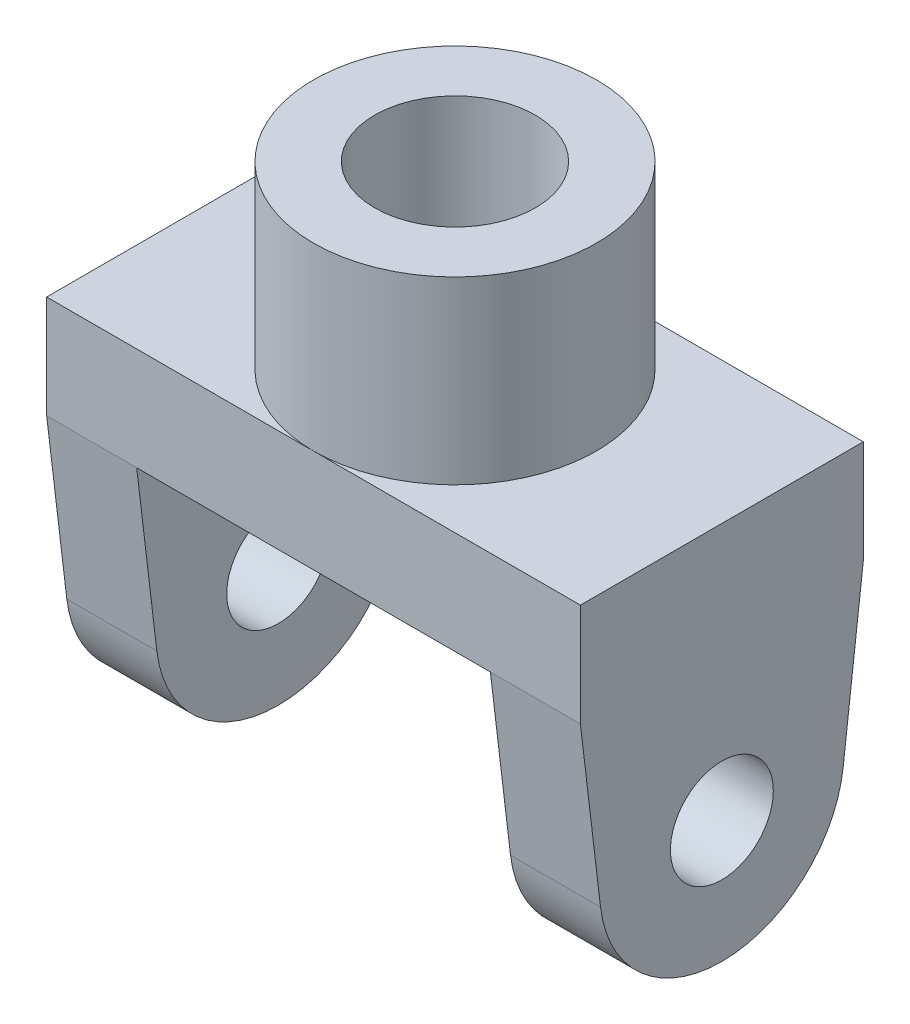
SolidWorks part; units mm, degrees
ref_plane "Front Plane" through (0, 0, 0) normal (0, 0, 1) x (1, 0, 0)
ref_plane "Top Plane" through (0, 0, 0) normal (0, 1, 0) x (1, 0, 0)
ref_plane "Right Plane" through (0, 0, 0) normal (1, 0, 0) x (0, 0, -1)
sketch "Sketch1" plane through (0, 0, 0) normal (0, 1, 0) x (1, 0, 0)
  line L1 (-83, 44) -> (83, 44)
  line L2 (-83, 44) -> (-83, -44)
  line L3 (-83, -44) -> (83, -44)
  line L4 (83, 44) -> (83, -44)
  line L5 (-83, 44) -> (83, -44) construction
  line L6 (-83, -44) -> (83, 44) construction
  point P0 (0, 0)
  dimension "D1" = 166
  dimension "D2" = 88
extrude "Boss-Extrude1" add sketch "Sketch1" along normal blind 32
sketch "Sketch2" plane through (0, 32, 0) normal (0, 1, 0) x (1, 0, 0)
  circle A0 centre (0, 0) radius 44
  circle A1 centre (0, 0) radius 25
  dimension "D1" = 50
extrude "Boss-Extrude2" add sketch "Sketch2" along normal blind 56
sketch "Sketch3" plane through (83, 0, 0) normal (1, 0, 0) x (0, 0, -1)
  line L1 (37.7321, -52.5044) -> (44, 0)
  line L2 (-37.7321, -52.5044) -> (-44, 0)
  line L3 (25, 88) -> (-25, 88) construction
  arc A0 (-37.7321, -52.5044) -> (37.7321, -52.5044) centre (0, -48) ccw
  circle A1 centre (0, -48) radius 16
  line M1 (-44, 0) -> (44, 0)
  dimension "D2" = 32
  dimension "D3" = 76
  dimension "D1" = 136
extrude "Boss-Extrude3" add sketch "Sketch3" against normal blind 28 contours L2 A0 L1 A1 M1
mirror "Mirror1" about plane through (0, 0, 0) normal (1, 0, 0) of "Boss-Extrude3"
